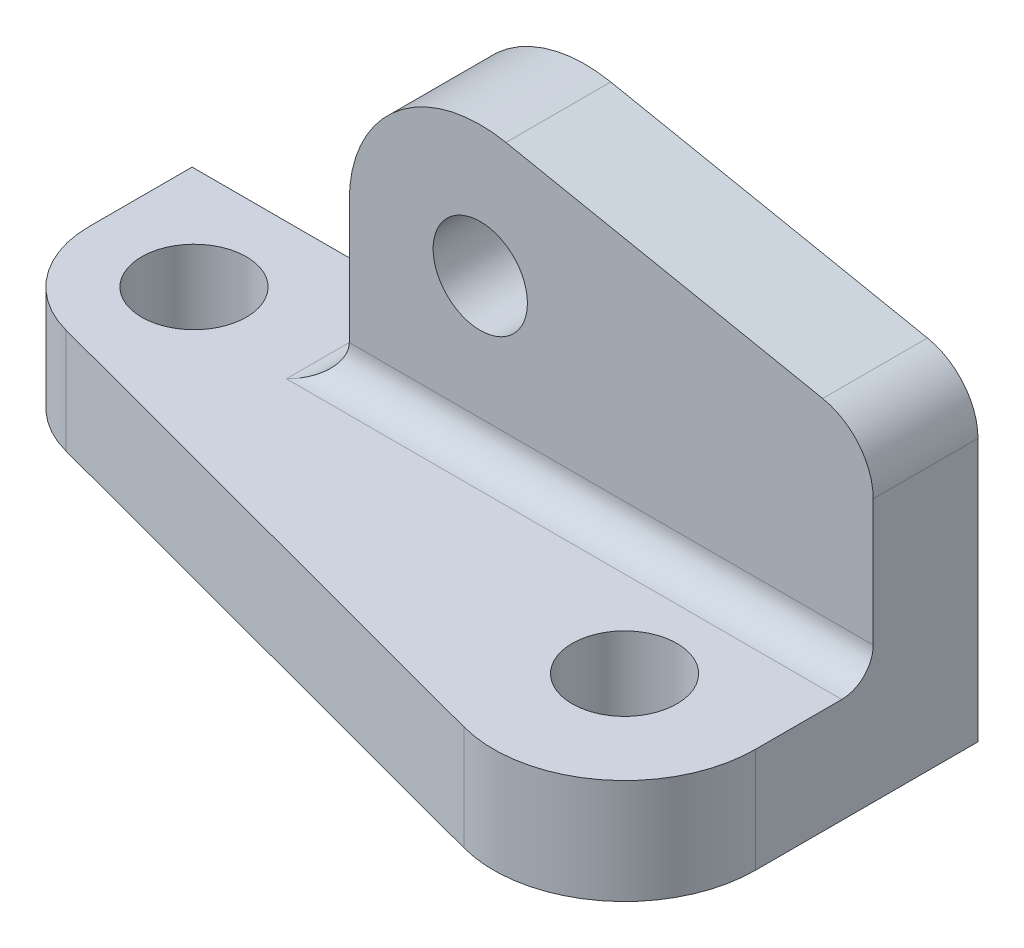
SolidWorks part; units mm, degrees
material "Plain Carbon Steel"
ref_plane "Front Plane" through (0, 0, 0) normal (0, 0, 1) x (1, 0, 0)
ref_plane "Top Plane" through (0, 0, 0) normal (0, 1, 0) x (1, 0, 0)
ref_plane "Right Plane" through (0, 0, 0) normal (1, 0, 0) x (0, 0, -1)
sketch "Sketch1" plane through (0, 0, 0) normal (0, 1, 0) x (1, 0, 0)
  line L1 (0, 0) -> (150, 0)
  line L2 (0, 0) -> (0, -35)
  line L3 (0, -35) -> (150, -75)
  line L4 (150, 0) -> (150, -75)
  dimension "D1" = 150
  dimension "D2" = 75
  dimension "D3" = 35
extrude "Extrude1" add sketch "Sketch1" along normal blind 20
sketch "Sketch2" plane through (0, 0, 0) normal (0, 0, -1) x (-1, 0, 0)
  line L1 (-150, 0) -> (-50, 0)
  line L2 (-150, 0) -> (-150, 60)
  line L3 (-150, 60) -> (-50, 80)
  line L4 (-50, 0) -> (-50, 80)
  dimension "D1" = 100
  dimension "D2" = 80
  dimension "D3" = 60
extrude "Extrude2" add sketch "Sketch2" against normal blind 20
fillet "Fillet1" radius 25 2 edges at (50, 80, 10) (150, 10, 75)
fillet "Fillet2" radius 20 1 edges at (0, 10, 35)
fillet "Fillet3" radius 12 1 edges at (150, 60, 10)
fillet "Fillet4" radius 6 2 edges at (50, 20, 10) (100, 20, 20)
hole_wizard "M20.0 (20) Diameter Hole1" positions "Sketch4" profile "Sketch3" hole size "M20.0" standard "Ansi Metric" end condition through all
sketch "Sketch4" plane through (0, 20, 0) normal (0, 1, 0) x (-1, 0, 0)
  arc A0 (0, 19.6344) -> (-14.8467, 38.9591) centre (-20, 19.6344) ccw construction
  arc A1 (-118.5584, 66.6156) -> (-150, 42.4597) centre (-125, 42.4597) ccw construction
  point P0 (-125, 42.4597)
  point P1 (-20, 19.6344)
sketch "Sketch3" plane through (125, 20, 42.4597) normal (1, 0, 0) x (0, 0, 1)
  line L0 (0, 0) -> (0, 20)
  line L1 (0, 20) -> (10, 20)
  line L2 (10, 20) -> (10, 0)
  line L5 (10, 0) -> (0, 0)
  line L11 (0, -6.35) -> (0, 107.95) construction
  dimension "Thru Hole Dia." = 20
  dimension "Thru Hole Depth" = 20
hole_wizard "M18.0 (18) Diameter Hole1" positions "Sketch5" profile "Sketch6" hole size "M18.0" standard "Ansi Metric" end condition through all
sketch "Sketch5" plane through (130.8799, 20.2642, 20) normal (0, 0, 1) x (1, 0, 0)
  arc A2 (-50.977, 53.7552) -> (-80.8799, 29.2407) centre (-55.8799, 29.2407) ccw construction
  point P1 (-55.8799, 29.2407)
sketch "Sketch6" plane through (75, 49.5049, 20) normal (1, 0, 0) x (0, -1, 0)
  line L0 (0, 0) -> (0, 20)
  line L1 (0, 20) -> (9, 20)
  line L2 (9, 20) -> (9, 0)
  line L5 (9, 0) -> (0, 0)
  line L11 (0, -6.35) -> (0, 107.95) construction
  dimension "Thru Hole Dia." = 18
  dimension "Thru Hole Depth" = 20
